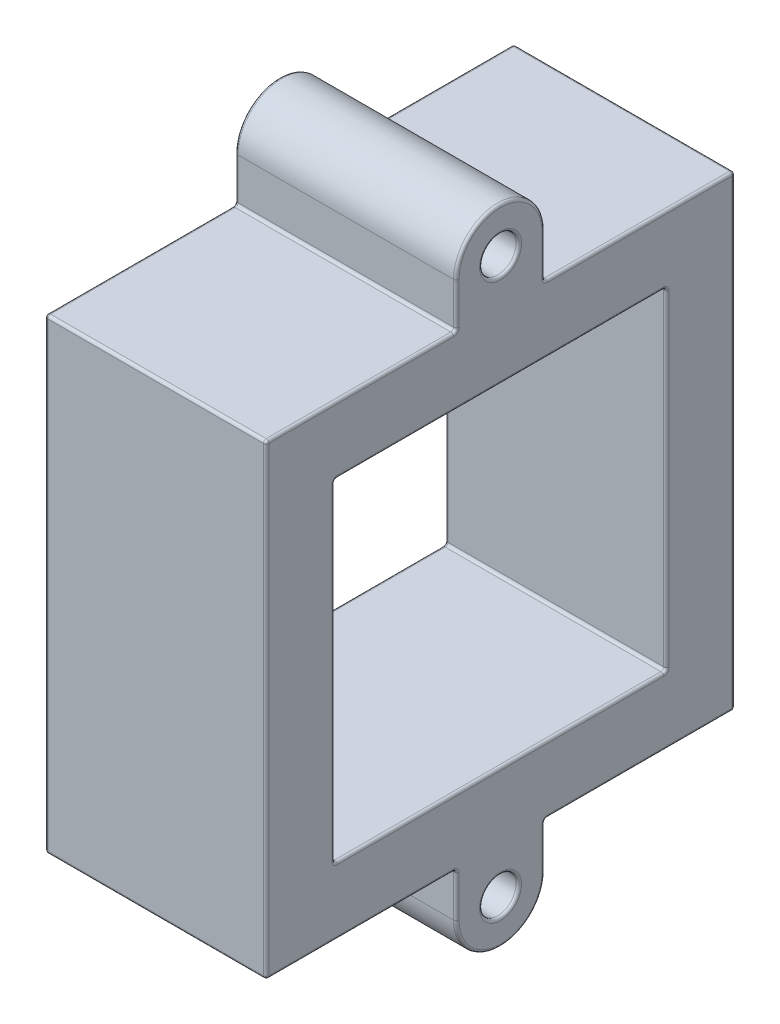
SolidWorks part; units mm, degrees
ref_plane "Front Plane" through (0, 0, 0) normal (1, 0, 0) x (0, 1, 0)
ref_plane "Top Plane" through (0, 0, 0) normal (0, 0, 1) x (0, 1, 0)
ref_plane "Right Plane" through (0, 0, 0) normal (0, 1, 0) x (-1, 0, 0)
sketch "Sketch1" plane through (0, 0, 0) normal (1, 0, 0) x (0, 1, 0)
  line L0 (-25.1, 4) -> (-21.1, 4)
  line L1 (-15, 15) -> (15, 15)
  line L2 (-15, 15) -> (-15, -15)
  line L3 (-15, -15) -> (15, -15)
  line L4 (15, 15) -> (15, -15)
  line L5 (-15, 15) -> (15, -15) construction
  line L6 (-15, -15) -> (15, 15) construction
  line L7 (-21.1, 21.2) -> (21.1, 21.2)
  line L8 (-21.1, 21.2) -> (-21.1, 4)
  line L9 (-21.1, -21.2) -> (21.1, -21.2)
  line L10 (21.1, 21.2) -> (21.1, 4)
  line L11 (-21.1, 21.2) -> (21.1, -21.2) construction
  line L12 (-21.1, -21.2) -> (21.1, 21.2) construction
  line L13 (-25.1, -4) -> (-21.1, -4)
  line L14 (0, 31.084) -> (0, -25.7946) construction
  line L15 (25.1, -4) -> (21.1, -4)
  line L16 (25.1, 4) -> (21.1, 4)
  line L17 (-21.1, -4) -> (-21.1, -21.2)
  line L18 (21.1, -4) -> (21.1, -21.2)
  circle A0 centre (-25.1, 0) radius 1.65
  arc A1 (-25.1, 4) -> (-25.1, -4) centre (-25.1, 0) ccw
  circle A2 centre (25.1, 0) radius 1.65
  arc A3 (25.1, 4) -> (25.1, -4) centre (25.1, 0) cw
  point P0 (0, 0)
  point P6 (0, 0)
  dimension "D5" = 3.3
  dimension "D1" = 30
  dimension "D2" = 30
  dimension "D3" = 42.2
  dimension "D4" = 42.4
  dimension "D6" = 4
extrude "Boss-Extrude1" add sketch "Sketch1" along normal blind 20
fillet "Fillet18" radius 0.25 48 edges at (0, 25.1, 1.65) (20, 25.1, 1.65) (0, -25.1, -1.65) (20, -25.1, -1.65) (0, 15, 0) (0, 0, 15) (0, -15, 0) (0, 0, -15) (20, 15, 0) (20, 0, 15) (20, -15, 0) (20, 0, -15) (10, 15, -15) (10, -15, -15) (10, -15, 15) (10, 15, 15) (0, 21.1, -12.6) (0, 23.1, -4) (0, 29.1, 0) (0, 23.1, 4) (0, 21.1, 12.6) (0, 0, 21.2) (0, -21.1, 12.6) (0, -23.1, 4) (0, -29.1, 0) (0, -23.1, -4) (0, -21.1, -12.6) (0, 0, -21.2) (20, 21.1, -12.6) (20, 23.1, -4) (20, 29.1, 0) (20, 23.1, 4) (20, 21.1, 12.6) (20, 0, 21.2) (20, -21.1, 12.6) (20, -23.1, 4) (20, -29.1, 0) (20, -23.1, -4) (20, -21.1, -12.6) (20, 0, -21.2) (10, 21.1, -21.2) (10, -21.1, -21.2) (10, -21.1, -4) (10, -21.1, 4) (10, -21.1, 21.2) (10, 21.1, 21.2) (10, 21.1, 4) (10, 21.1, -4)
